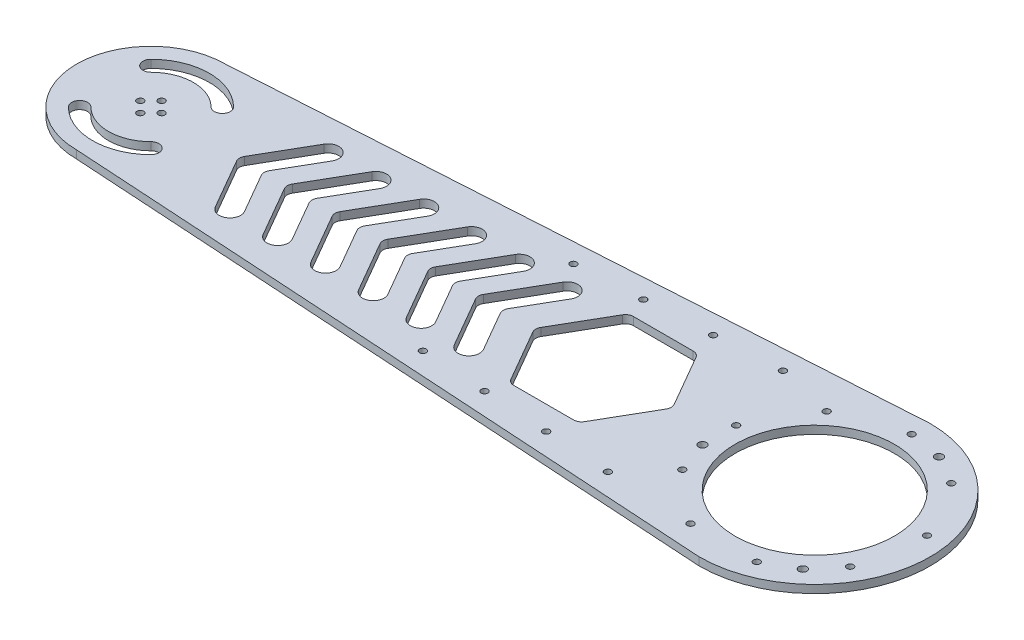
SolidWorks part; units mm, degrees
material "6061 合金"
ref_plane "前视基准面" through (0, 0, 0) normal (0, 0, 1) x (1, 0, 0)
ref_plane "上视基准面" through (0, 0, 0) normal (0, 1, 0) x (1, 0, 0)
ref_plane "右视基准面" through (0, 0, 0) normal (1, 0, 0) x (0, 0, -1)
other "Configuration Table"
sketch "草图1" plane through (0, 0, 0) normal (0, 1, 0) x (1, 0, 0)
  line L0 (0, -43.5) -> (0, 43.5) construction
  line L1 (0, 0) -> (-27.9613, 33.3229) construction
  line L2 (0, 0) -> (27.9613, 33.3229) construction
  line L3 (0, 0) -> (14.8779, 40.8766) construction
  line L4 (0, 0) -> (-250, 0) construction
  line L5 (-230.201, -19.799) -> (-269.799, 19.799) construction
  line L6 (-269.799, -19.799) -> (-230.201, 19.799) construction
  line L7 (0, 28) -> (-250, 28) construction
  line L8 (0, 28) -> (0, -28) construction
  line L9 (0, -28) -> (-250, -28) construction
  line L10 (-250, 28) -> (-250, -28) construction
  line L11 (-125, -28) -> (-125, 28) construction
  line L12 (0, 0) -> (-250, 0) construction
  line L13 (-250, 0) -> (-250, 18.6396) construction
  line L14 (-250, 0) -> (-236.565, 13.435) construction
  line L15 (-250, 0) -> (-263.435, 13.435) construction
  line L16 (-250, 28) -> (0, 43.5) construction
  line L17 (-250, -28) -> (0, -43.5) construction
  circle A0 centre (0, 0) radius 43.5 construction
  circle A1 centre (0, 0) radius 36.5 construction
  circle A2 centre (0, 0) radius 30 construction
  circle A7 centre (-23.4617, 27.9606) radius 1.25 construction
  circle A8 centre (0, 36.5) radius 1.25 construction
  circle A9 centre (12.4837, 34.2988) radius 1.5 construction
  circle A10 centre (23.4617, 27.9606) radius 1.25 construction
  circle A11 centre (35.9455, 6.3382) radius 1.25 construction
  circle A12 centre (31.6099, -18.25) radius 1.25 construction
  circle A13 centre (23.4617, -27.9606) radius 1.5 construction
  circle A14 centre (12.4837, -34.2988) radius 1.25 construction
  circle A15 centre (-12.4837, -34.2988) radius 1.25 construction
  circle A16 centre (-31.6099, -18.25) radius 1.25 construction
  circle A17 centre (-35.9455, -6.3382) radius 1.5 construction
  circle A18 centre (-35.9455, 6.3382) radius 1.25 construction
  circle A19 centre (-250, 0) radius 28 construction
  circle A20 centre (-250, 0) radius 22 construction
  circle A21 centre (-250, 0) radius 16 construction
  arc A22 (-263.435, 13.435) -> (-236.565, 13.435) centre (-250, 0) cw construction
  arc A23 (-234.4463, 15.5537) -> (-265.5537, 15.5537) centre (-250, 0) ccw construction
  arc A24 (-238.6836, 11.3164) -> (-261.3164, 11.3164) centre (-250, 0) ccw construction
  arc A25 (-238.6836, 11.3164) -> (-234.4463, 15.5537) centre (-236.565, 13.435) ccw construction
  arc A26 (-265.5537, 15.5537) -> (-261.3164, 11.3164) centre (-263.435, 13.435) ccw construction
  circle A27 centre (-250, 0) radius 4 construction
  circle A28 centre (-250, 4) radius 1.25 construction
  circle A29 centre (-254, 0) radius 1.25 construction
  circle A30 centre (-250, -4) radius 1.25 construction
  circle A31 centre (-246, 0) radius 1.25 construction
  arc A32 (-263.435, -13.435) -> (-236.565, -13.435) centre (-250, 0) ccw construction
  arc A33 (-234.4463, -15.5537) -> (-265.5537, -15.5537) centre (-250, 0) cw construction
  arc A34 (-238.6836, -11.3164) -> (-261.3164, -11.3164) centre (-250, 0) cw construction
  arc A35 (-238.6836, -11.3164) -> (-234.4463, -15.5537) centre (-236.565, -13.435) cw construction
  arc A36 (-265.5537, -15.5537) -> (-261.3164, -11.3164) centre (-263.435, -13.435) cw construction
  point P8 (0, 0)
  point P24 (-125, 0)
  point P42 (0, 0)
  point P44 (-250, 0)
  point P53 (-250, 19)
  point P71 (-250, -19)
  dimension "D1" = 3
ref_plane "基准面1" through (0, 5, 0) normal (0, 1, 0) x (1, 0, 0)
sketch "草图2" plane through (0, 5, 0) normal (0, 1, 0) x (1, 0, 0)
  line L0 (-250, 28) -> (0, 43.5)
  line L1 (-250, -28) -> (0, -43.5)
  arc A0 (-250, 28) -> (-250, -28) centre (-250, 0) ccw
  arc A1 (0, 43.5) -> (0, -43.5) centre (0, 0) cw
extrude "凸台-拉伸1" add sketch "草图2" along normal blind 3
sketch3d "3D草图1"
  point P0 (-145.9567, 8, -3.4646)
ref_plane "基准面2" through (0, 8, 0) normal (0, 1, 0) x (1, 0, 0)
sketch "草图3" plane through (0, 8, 0) normal (0, 1, 0) x (1, 0, 0)
  circle A0 centre (-250, 4) radius 1.25
  circle A1 centre (-246, 0) radius 1.25
  circle A2 centre (-250, -4) radius 1.25
  circle A3 centre (-254, 0) radius 1.25
  circle A4 centre (0, 0) radius 30
  circle A5 centre (0, 36.5) radius 1.25
  circle A6 centre (12.4837, 34.2988) radius 1.5
  circle A7 centre (23.4617, 27.9606) radius 1.25
  circle A8 centre (-23.4617, 27.9606) radius 1.25
  circle A9 centre (-35.9455, 6.3382) radius 1.25
  circle A10 centre (-35.9455, -6.3382) radius 1.5
  circle A11 centre (-31.6099, -18.25) radius 1.25
  circle A12 centre (-12.4837, -34.2988) radius 1.25
  circle A13 centre (12.4837, -34.2988) radius 1.25
  circle A14 centre (23.4617, -27.9606) radius 1.5
  circle A15 centre (31.6099, -18.25) radius 1.25
  circle A16 centre (35.9455, 6.3382) radius 1.25
  arc A17 (-265.5537, 15.5537) -> (-261.3164, 11.3164) centre (-263.435, 13.435) ccw
  arc A18 (-238.6836, 11.3164) -> (-234.4463, 15.5537) centre (-236.565, 13.435) ccw
  arc A19 (-234.4463, 15.5537) -> (-265.5537, 15.5537) centre (-250, 0) ccw
  arc A20 (-261.3164, 11.3164) -> (-238.6836, 11.3164) centre (-250, 0) cw
  arc A21 (-261.3164, -11.3164) -> (-238.6836, -11.3164) centre (-250, 0) ccw
  arc A22 (-234.4463, -15.5537) -> (-265.5537, -15.5537) centre (-250, 0) cw
  arc A23 (-265.5537, -15.5537) -> (-261.3164, -11.3164) centre (-263.435, -13.435) cw
  arc A24 (-238.6836, -11.3164) -> (-234.4463, -15.5537) centre (-236.565, -13.435) cw
extrude "切除-拉伸1" cut sketch "草图3" against normal blind 3
sketch3d "3D草图2"
  point P0 (-118.6358, 8, -10.1958)
ref_plane "基准面3" through (0, 8, 0) normal (0, 1, 0) x (1, 0, 0)
sketch "草图4" plane through (0, 8, 0) normal (0, 1, 0) x (1, 0, 0)
  line L0 (0, 0) -> (-250, 0) construction
  line L1 (-222.1049, 0) -> (-217.1049, 0) construction
  line L3 (-217.1049, 0) -> (-210.1249, -4.0299) construction
  line L4 (-217.1049, 0) -> (-205.2675, 20.5031) construction
  line L5 (-205.2675, 20.5031) -> (-198.2874, 16.4731) construction
  line L6 (-210.1249, -4.0299) -> (-198.2874, 16.4731) construction
  line L7 (-217.1049, 0) -> (-198.2874, 16.4731) construction
  line L8 (-205.2675, 20.5031) -> (-210.1249, -4.0299) construction
  line L28 (-214.6027, 0) -> (-194.6027, 0) construction
  line L29 (-115.7976, 0) -> (-43.3199, 0) construction
  line L30 (-216.2389, 1.5) -> (-205.2675, 20.5031)
  line L31 (-54.444, 1.5) -> (-65.7024, 21)
  line L32 (-68.3004, 22.5) -> (-90.8171, 22.5)
  line L33 (-93.4152, 21) -> (-104.6735, 1.5)
  line L34 (-104.6735, -1.5) -> (-93.4152, -21)
  line L35 (-90.8171, -22.5) -> (-68.3004, -22.5)
  line L36 (-65.7024, -21) -> (-54.444, -1.5)
  line L37 (-206.9322, 1.5) -> (-198.2874, 16.4731)
  line L38 (-206.9322, -1.5) -> (-198.2874, -16.4731)
  line L39 (-216.2389, -1.5) -> (-205.2675, -20.5031)
  line L40 (-188.9322, -1.5) -> (-180.2874, -16.4731)
  line L41 (-198.2389, -1.5) -> (-187.2675, -20.5031)
  line L42 (-198.2389, 1.5) -> (-187.2675, 20.5031)
  line L43 (-188.9322, 1.5) -> (-180.2874, 16.4731)
  line L44 (-170.9322, -1.5) -> (-162.2874, -16.4731)
  line L45 (-180.2389, -1.5) -> (-169.2675, -20.5031)
  line L46 (-180.2389, 1.5) -> (-169.2675, 20.5031)
  line L47 (-170.9322, 1.5) -> (-162.2874, 16.4731)
  line L48 (-152.9322, -1.5) -> (-144.2874, -16.4731)
  line L49 (-162.2389, -1.5) -> (-151.2675, -20.5031)
  line L50 (-162.2389, 1.5) -> (-151.2675, 20.5031)
  line L51 (-152.9322, 1.5) -> (-144.2874, 16.4731)
  line L52 (-134.9322, -1.5) -> (-126.2874, -16.4731)
  line L53 (-144.2389, -1.5) -> (-133.2675, -20.5031)
  line L54 (-144.2389, 1.5) -> (-133.2675, 20.5031)
  line L55 (-134.9322, 1.5) -> (-126.2874, 16.4731)
  line L56 (-116.9322, -1.5) -> (-108.2874, -16.4731)
  line L57 (-126.2389, -1.5) -> (-115.2675, -20.5031)
  line L58 (-126.2389, 1.5) -> (-115.2675, 20.5031)
  line L59 (-116.9322, 1.5) -> (-108.2874, 16.4731)
  line L60 (-206.9322, -1.5) -> (-188.9322, -1.5) construction
  arc A0 (-205.2675, 20.5031) -> (-198.2874, 16.4731) centre (-201.7775, 18.4881) cw construction
  circle A21 centre (-79.5588, 0) radius 22.5 construction
  arc A22 (-93.4152, 21) -> (-90.8171, 22.5) centre (-90.8171, 19.5) cw
  arc A23 (-104.6735, -1.5) -> (-104.6735, 1.5) centre (-102.0754, 0) cw
  arc A24 (-90.8171, -22.5) -> (-93.4152, -21) centre (-90.8171, -19.5) cw
  arc A25 (-65.7024, -21) -> (-68.3004, -22.5) centre (-68.3004, -19.5) cw
  arc A26 (-54.444, 1.5) -> (-54.444, -1.5) centre (-57.0421, 0) cw
  arc A27 (-65.7024, 21) -> (-68.3004, 22.5) centre (-68.3004, 19.5) ccw
  arc A28 (-205.2675, 20.5031) -> (-198.2874, 16.4731) centre (-201.7775, 18.4881) cw
  arc A29 (-205.2675, -20.5031) -> (-198.2874, -16.4731) centre (-201.7775, -18.4881) ccw
  arc A30 (-216.2389, -1.5) -> (-216.2389, 1.5) centre (-213.6408, 0) cw
  arc A31 (-206.9322, -1.5) -> (-206.9322, 1.5) centre (-204.3341, 0) cw
  arc A32 (-188.9322, -1.5) -> (-188.9322, 1.5) centre (-186.3341, 0) cw
  arc A33 (-187.2675, -20.5031) -> (-180.2874, -16.4731) centre (-183.7775, -18.4881) ccw
  arc A34 (-198.2389, -1.5) -> (-198.2389, 1.5) centre (-195.6408, 0) cw
  arc A35 (-187.2675, 20.5031) -> (-180.2874, 16.4731) centre (-183.7775, 18.4881) cw
  arc A36 (-170.9322, -1.5) -> (-170.9322, 1.5) centre (-168.3341, 0) cw
  arc A37 (-169.2675, -20.5031) -> (-162.2874, -16.4731) centre (-165.7775, -18.4881) ccw
  arc A38 (-180.2389, -1.5) -> (-180.2389, 1.5) centre (-177.6408, 0) cw
  arc A39 (-169.2675, 20.5031) -> (-162.2874, 16.4731) centre (-165.7775, 18.4881) cw
  arc A40 (-152.9322, -1.5) -> (-152.9322, 1.5) centre (-150.3341, 0) cw
  arc A41 (-151.2675, -20.5031) -> (-144.2874, -16.4731) centre (-147.7775, -18.4881) ccw
  arc A42 (-162.2389, -1.5) -> (-162.2389, 1.5) centre (-159.6408, 0) cw
  arc A43 (-151.2675, 20.5031) -> (-144.2874, 16.4731) centre (-147.7775, 18.4881) cw
  arc A44 (-134.9322, -1.5) -> (-134.9322, 1.5) centre (-132.3341, 0) cw
  arc A45 (-133.2675, -20.5031) -> (-126.2874, -16.4731) centre (-129.7775, -18.4881) ccw
  arc A46 (-144.2389, -1.5) -> (-144.2389, 1.5) centre (-141.6408, 0) cw
  arc A47 (-133.2675, 20.5031) -> (-126.2874, 16.4731) centre (-129.7775, 18.4881) cw
  arc A48 (-116.9322, -1.5) -> (-116.9322, 1.5) centre (-114.3341, 0) cw
  arc A49 (-115.2675, -20.5031) -> (-108.2874, -16.4731) centre (-111.7775, -18.4881) ccw
  arc A50 (-126.2389, -1.5) -> (-126.2389, 1.5) centre (-123.6408, 0) cw
  arc A51 (-115.2675, 20.5031) -> (-108.2874, 16.4731) centre (-111.7775, 18.4881) cw
  point P19 (-207.7982, 0)
  point P23 (-207.7982, 0)
  dimension "D2" = 3
  dimension "D5" = 3
  dimension "D6" = 3
  dimension "D7" = 3
  dimension "D8" = 3
  dimension "D9" = 3
  dimension "D10" = 3
  dimension "D11" = 18
  dimension "D3" = 3
  dimension "D4" = 6
extrude "切除-拉伸2" cut sketch "草图4" against normal blind 3
ref_plane "基准面4" through (0, 8, 0) normal (0, 1, 0) x (1, 0, 0)
sketch "草图5" plane through (0, 8, 0) normal (0, 1, 0) x (1, 0, 0)
  line L0 (-125, 0) -> (-43.5, 0) construction
  line L5 (-125, 28) -> (-27.1878, 34.0644) construction
  line L6 (0, 0) -> (-250, 0) construction
  line L11 (-250, 28) -> (0, 43.5) construction
  circle A3 centre (-44.9417, 32.9636) radius 1.25
  circle A4 centre (-69.7029, 31.4284) radius 1.25
  circle A7 centre (-119.2253, 28.358) radius 1.25
  circle A8 centre (-94.4641, 29.8932) radius 1.25
  circle A9 centre (0, 0) radius 43.5 construction
  circle A10 centre (-44.9417, -32.9636) radius 1.25
  circle A11 centre (-69.7029, -31.4284) radius 1.25
  circle A12 centre (-94.4641, -29.8932) radius 1.25
  circle A13 centre (-119.2253, -28.358) radius 1.25
  point P3 (-62.5299, 31.5812)
  point P4 (-62.5299, 31.5812)
extrude "切除-拉伸3" cut sketch "草图5" against normal blind 10
